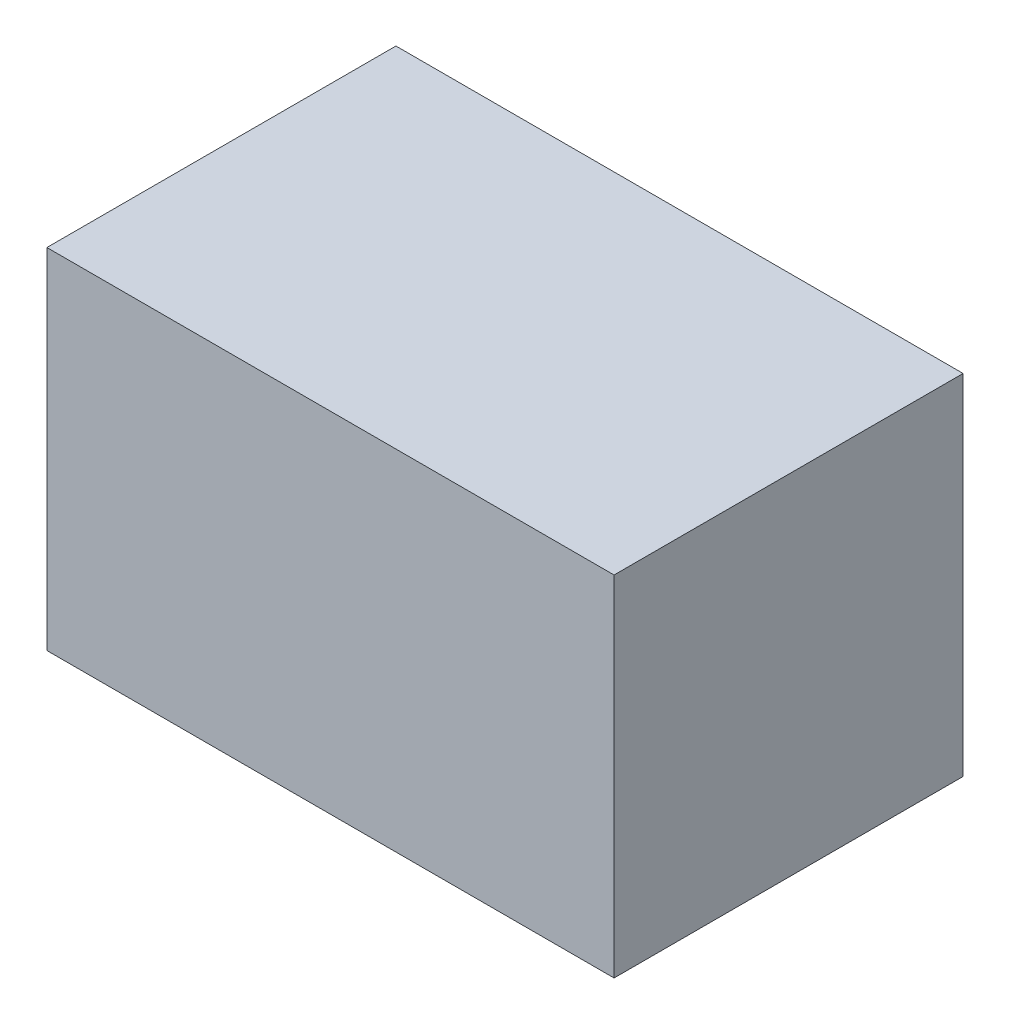
SolidWorks part; units mm, degrees
ref_plane "Front Plane" through (0, 0, 0) normal (0, 0, 1) x (1, 0, 0)
ref_plane "Top Plane" through (0, 0, 0) normal (0, 1, 0) x (1, 0, 0)
ref_plane "Right Plane" through (0, 0, 0) normal (1, 0, 0) x (0, 0, -1)
sketch "Sketch1" plane through (0, 0, 0) normal (0, 1, 0) x (1, 0, 0)
  line L1 (-165.1, 101.6) -> (165.1, 101.6)
  line L2 (-165.1, 101.6) -> (-165.1, -101.6)
  line L3 (-165.1, -101.6) -> (165.1, -101.6)
  line L4 (165.1, 101.6) -> (165.1, -101.6)
  line L5 (-165.1, 101.6) -> (165.1, -101.6) construction
  line L6 (-165.1, -101.6) -> (165.1, 101.6) construction
  point P0 (0, 0)
  dimension "D1" = 330.2
  dimension "D2" = 203.2
extrude "Boss-Extrude1" add sketch "Sketch1" along normal blind 203.2
